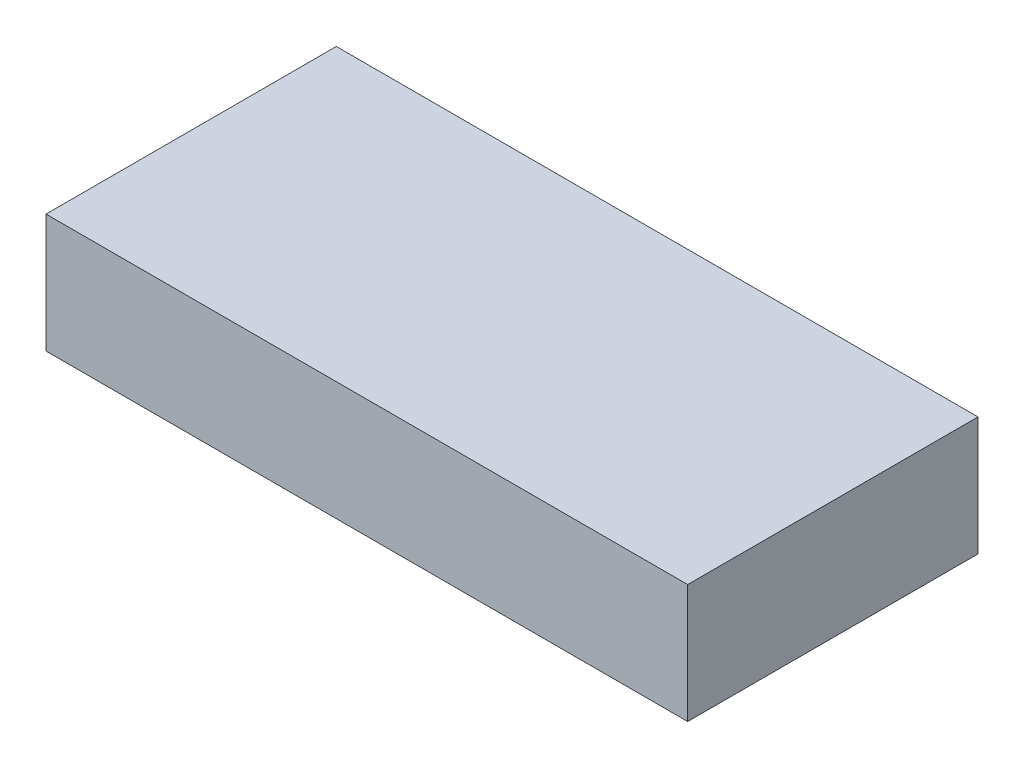
SolidWorks part; units mm, degrees
ref_plane "Front Plane" through (0, 0, 0) normal (0, 0, 1) x (1, 0, 0)
ref_plane "Top Plane" through (0, 0, 0) normal (0, 1, 0) x (1, 0, 0)
ref_plane "Right Plane" through (0, 0, 0) normal (1, 0, 0) x (0, 0, -1)
sketch "Sketch1" plane through (0, 0, 0) normal (0, 1, 0) x (1, 0, 0)
  line L1 (0, 0) -> (107.2, 0)
  line L2 (0, 0) -> (0, 48.5)
  line L3 (0, 48.5) -> (107.2, 48.5)
  line L4 (107.2, 0) -> (107.2, 48.5)
  dimension "D1" = 48.5
  dimension "D2" = 107.2
extrude "Boss-Extrude1" add sketch "Sketch1" along normal blind 19.82
